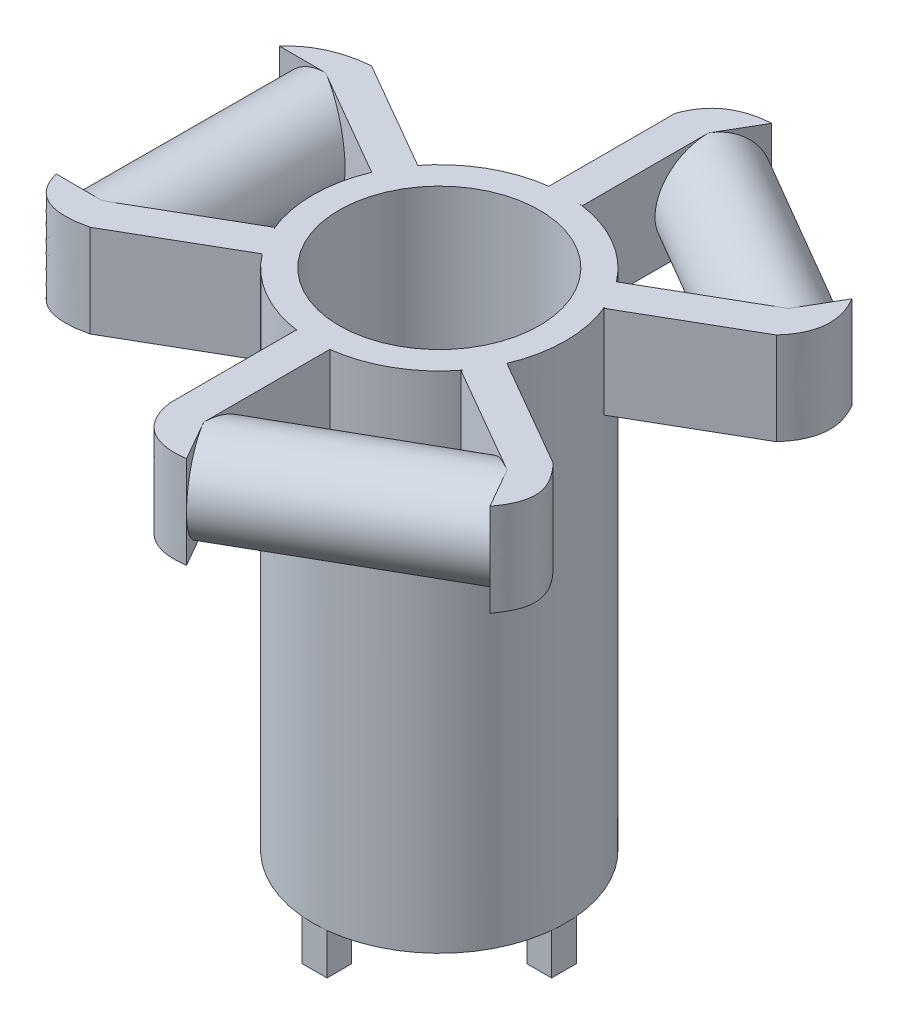
SolidWorks part; units mm, degrees
ref_plane "Front Plane" through (0, 0, 0) normal (0, 0, 1) x (1, 0, 0)
ref_plane "Top Plane" through (0, 0, 0) normal (0, 1, 0) x (1, 0, 0)
ref_plane "Right Plane" through (0, 0, 0) normal (1, 0, 0) x (0, 0, -1)
sketch "Sketch1" plane through (0, 0, 0) normal (0, 1, 0) x (1, 0, 0)
  circle A0 centre (0, 0) radius 7.5185
extrude "Boss-Extrude1" add sketch "Sketch1" along normal blind 30
sketch "Sketch5" plane through (0, 30, 0) normal (0, 1, 0) x (1, 0, 0)
  line L0 (3.7565, 6.5128) -> (-3.762, -6.5096) construction
  line L1 (-3.762, 6.5096) -> (3.7565, -6.5128) construction
  line L2 (-7.5185, 0) -> (7.5185, 0) construction
  line L3 (7.5185, 0) -> (11.5185, 0)
  line L4 (3.7565, 6.5128) -> (5.7673, 9.9707)
  circle A0 centre (0, 0) radius 7.5185 construction
  dimension "D1" = 60
  dimension "D2" = 60
  dimension "D3" = 4
  dimension "D4" = 4
sketch "Sketch7" plane through (0, 30, 0) normal (0, 1, 0) x (1, 0, 0)
  circle A0 centre (0, 0) radius 5.957
extrude "Cut-Extrude1" cut sketch "Sketch7" against normal blind 60
sketch "Sketch8" plane through (0, 30, 0) normal (0, 1, 0) x (1, 0, 0)
  line L1 (1.0555, 14.9589) -> (-0.9445, 14.9589)
  line L2 (1.0555, 14.9589) -> (1.0555, 7.4589)
  line L3 (1.0555, 7.4589) -> (-0.9445, 7.4589)
  line L4 (-0.9445, 14.9589) -> (-0.9445, 7.4589)
  line L5 (1.0555, 14.9589) -> (-0.9445, 7.4589) construction
  line L6 (1.0555, 7.4589) -> (-0.9445, 14.9589) construction
  circle A0 centre (0, 0) radius 7.5185 construction
  point P0 (0.0555, 11.2089)
  dimension "D1" = 7.5
  dimension "D2" = 2
extrude "Boss-Extrude4" add sketch "Sketch8" against normal blind 5.5
pattern_circular "CirPattern7" count 6 over 360 about axis through (0, 0, 0) along (0, 1, 0) of "Boss-Extrude4"
ref_plane "Plane4" through (6.6785, 0, 11.6804) normal (-0.4964, 0, -0.8681) x (-0.8681, 0, 0.4964)
sketch "Sketch13" plane through (6.6785, 0, 11.6804) normal (-0.4964, 0, -0.8681) x (-0.8681, 0, 0.4964)
  line L0 (6.6051, 27.25) -> (-6.6219, 27.25)
  line L1 (6.6051, 30) -> (-6.6219, 30)
  line L2 (6.6051, 30) -> (6.6051, 24.5)
  line L3 (6.6051, 24.5) -> (-6.6219, 24.5)
  line L4 (-6.6219, 30) -> (-6.6219, 24.5)
revolve "Revolve1" add sketch "Sketch13" angle 360 about L0
sketch "Sketch15" plane through (0, 30, 0) normal (0, 1, 0) x (1, 0, 0)
  line L0 (2.3095, -17.3462) -> (0.9445, -14.9589)
  line L1 (0.9445, -14.9589) -> (-1.0555, -14.9589)
  spline S0 degree 3 poles (-1.0555, -14.9589) (-0.8265, -16.6586) (0.3155, -17.6408) (2.3095, -17.3462) knots 0 0 0 0 1 1 1 1
extrude "Boss-Extrude6" add sketch "Sketch15" against normal blind 5.5 contours L0 L1 S0
sketch "Sketch20" plane through (0, 30, 0) normal (0, 1, 0) x (1, 0, 0)
  line L0 (13.7921, -10.7809) -> (12.4271, -8.3936)
  line L1 (9.3045, -10.1789) -> (4.0524, -13.1819) construction
  line L2 (13.7921, -10.7809) -> (12.4271, -8.3936) construction
  line L3 (12.4271, -8.3936) -> (13.4271, -6.6615)
  spline S0 degree 3 poles (13.4271, -6.6615) (14.9239, -8.1953) (14.8406, -9.356) (13.7921, -10.7809) knots 0 0 0 0 1 1 1 1
extrude "Boss-Extrude7" add sketch "Sketch20" against normal blind 5.516
pattern_circular "CirPattern10" count 3 over 360 about axis through (0, -30, 0) along (0, 1, 0) of "Revolve1"
sketch "Sketch21" plane through (0, 30, 0) normal (0, 1, 0) x (1, 0, 0)
  line L0 (-16.2325, -6.5538) -> (-13.4826, -6.5654) construction
  line L1 (-16.2325, -6.5538) -> (-13.4826, -6.5654)
  line L2 (-13.4826, -6.5654) -> (-12.4826, -8.2974)
  spline S0 degree 2 poles (-12.4826, -8.2974) (-15.6047, -9.033) (-16.2325, -6.5538) knots 0 0 0 1 1 1
extrude "Boss-Extrude8" add sketch "Sketch21" against normal blind 5.5 contours L2 S0 L1
ref_plane "Plane5" through (0, 30, 0) normal (0, 1, 0) x (1, 0, 0)
sketch "Sketch24" plane through (0, 30, 0) normal (0, 1, 0) x (1, 0, 0)
  line L1 (-13.4271, 6.6615) -> (-16.177, 6.673)
  line L2 (-13.4271, 6.6615) -> (-12.4271, 8.3936)
  spline S0 degree 2 poles (-12.4271, 8.3936) (-14.8381, 8.1815) (-16.177, 6.673) knots 0 0 0 1 1 1
extrude "Boss-Extrude11" add sketch "Sketch24" against normal blind 5.5
ref_plane "Plane6" through (0, 30, 0) normal (0, 1, 0) x (1, 0, 0)
sketch "Sketch26" plane through (0, 30, 0) normal (0, 1, 0) x (1, 0, 0)
  line L0 (13.8675, 10.6732) -> (12.4826, 8.2974)
  line L1 (12.4826, 8.2974) -> (13.4826, 6.5654)
  spline S0 degree 2 poles (13.4826, 6.5654) (15.1876, 8.4433) (13.8675, 10.6732) knots 0 0 0 1 1 1
extrude "Boss-Extrude12" add sketch "Sketch26" against normal blind 5.5
sketch "Sketch27" plane through (0, 30, 0) normal (0, 1, 0) x (1, 0, 0)
  line L0 (-0.9445, 14.9589) -> (1.0555, 14.9589)
  line L1 (1.0555, 14.9589) -> (2.4405, 17.3347)
  spline S0 degree 2 poles (-0.9445, 14.9589) (-0.1895, 17.1734) (2.4405, 17.3347) knots 0 0 0 1 1 1
extrude "Boss-Extrude13" add sketch "Sketch27" against normal blind 5.5
sketch "Sketch30" plane through (0, 0, 0) normal (0, -1, 0) x (-1, 0, 0)
  line L0 (0, 0) -> (0, -7.5185) construction
  line L2 (-0.7467, -5.9594) -> (0.7467, -5.9594)
  line L3 (-0.7467, -5.9594) -> (-0.7467, -7.4255)
  line L4 (-0.7467, -7.4255) -> (0.7467, -7.4255)
  line L5 (0.7467, -5.9594) -> (0.7467, -7.4255)
  line L6 (-0.7467, -5.9594) -> (0.7467, -7.4255) construction
  line L7 (-0.7467, -7.4255) -> (0.7467, -5.9594) construction
  arc A0 (-0.9445, -7.4589) -> (0.9445, -7.4589) centre (0, 0) ccw construction
  point P6 (0, -6.6925)
  point P11 (0, -6.6729)
  point P12 (0, -6.6925)
  point P13 (0, 0)
extrude "Boss-Extrude15" add sketch "Sketch30" along normal blind 2.5 contours L3 L2 L5 L4
pattern_circular "CirPattern11" count 4 over 360 about axis through (0, 0, 0) along (0, 1, 0) of "Boss-Extrude15"
